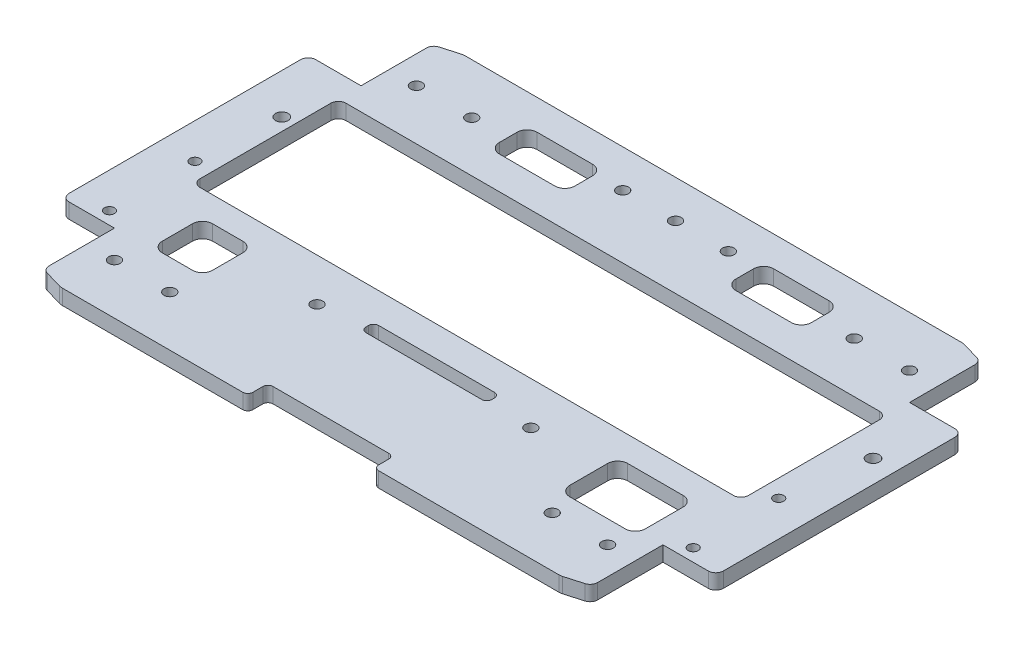
SolidWorks part; units mm, degrees
ref_plane "Plan de face" through (0, 0, 0) normal (0, 0, 1) x (1, 0, 0)
ref_plane "Plan de dessus" through (0, 0, 0) normal (0, 1, 0) x (1, 0, 0)
ref_plane "Plan de droite" through (0, 0, 0) normal (1, 0, 0) x (0, 0, -1)
sketch "Esquisse1" plane through (0, 0, 0) normal (0, 1, 0) x (1, 0, 0)
  line L0 (0, 0) -> (135, 0) construction
  line L1 (0, 0) -> (-135, 0) construction
  line L2 (-135, 0) -> (-135, -75)
  line L3 (-135, -85) -> (135, -85) construction
  line L4 (135, 0) -> (135, 75)
  line L5 (0, 85) -> (0, -85) construction
  line L6 (135, 85) -> (-135, 85) construction
  line L24 (0, -85) -> (-100, -85)
  line L26 (0, -85) -> (100, -85)
  line L28 (135, 0) -> (135, -75)
  line L31 (0, 85) -> (-100, 85)
  line L32 (0, 85) -> (100, 85)
  line L34 (-135, 0) -> (-135, 75)
  line L35 (-135, -75) -> (-100, -85)
  line L37 (-135, 75) -> (-100, 85)
  line L38 (100, 85) -> (135, 75)
  line L39 (100, -85) -> (135, -75)
  line L40 (-135, 75) -> (-100, 75) construction
  line L41 (-100, 75) -> (-100, 85) construction
  dimension "D1" = 10
  dimension "D2" = 200
  dimension "D3" = 10
  dimension "D4" = 200
  dimension "D5" = 75
  dimension "D6" = 35
  dimension "D7" = 75
  dimension "D8" = 170
extrude "Boss.-Extru.1" add sketch "Esquisse1" along normal blind 6
sketch "Esquisse15" plane through (0, 6, 0) normal (0, 1, 0) x (1, 0, 0)
  line L0 (-135, 60) -> (-135, 75)
  line L1 (-135, 60) -> (-120, 60) construction
  line L2 (-135, -60) -> (-120, -60) construction
  line L4 (-135, -60) -> (-135, -75)
  line L5 (-100, 85) -> (-135, 75) construction
  line L6 (-135, 75) -> (-135, -75) construction
  circle A0 centre (-120, 60) radius 2.3
  circle A1 centre (-120, -60) radius 2.3
extrude "Enlèv. mat.-Extru.6" cut sketch "Esquisse15" against normal up to next contours A1 | A0
mirror "Symétrie5" about plane through (0, 0, 0) normal (1, 0, 0) of "Enlèv. mat.-Extru.6"
sketch "Esquisse17" plane through (0, 6, 0) normal (0, 1, 0) x (1, 0, 0)
  line L0 (0, -85) -> (0, -71) construction
  line L1 (-100, -85) -> (100, -85) construction
  line L2 (-3.3, 0) -> (3.3, 0) construction
  line L4 (0, 85) -> (0, 71) construction
  circle A0 centre (0, -71) radius 2.3
  circle A3 centre (10, -71) radius 2.3
  circle A5 centre (-10, -71) radius 2.3
  circle A6 centre (30, -71) radius 2.3
  circle A7 centre (50, -71) radius 2.3
  circle A9 centre (90, -71) radius 2.3
  circle A11 centre (-50, -71) radius 2.3
  circle A13 centre (-90, -71) radius 2.3
  circle A14 centre (-90, 71) radius 2.3
  circle A16 centre (-50, 71) radius 2.3
  circle A17 centre (-30, 71) radius 2.3
  circle A18 centre (90, 71) radius 2.3
  circle A20 centre (50, 71) radius 2.3
  circle A21 centre (30, 71) radius 2.3
  circle A22 centre (-10, 71) radius 2.3
  circle A23 centre (10, 71) radius 2.3
  circle A24 centre (0, 71) radius 2.3
  circle A25 centre (-70, -71) radius 2.3 [skipped]
  circle A26 centre (70, -71) radius 2.3 [skipped]
  circle A27 centre (-70, -71) radius 2.3
  circle A28 centre (-30, -71) radius 2.3
  circle A29 centre (70, -71) radius 2.3
  circle A30 centre (70, 71) radius 2.3
  circle A31 centre (-70, 71) radius 2.3
  circle A32 centre (-30, -71) radius 2.3 [skipped]
  dimension "D1" = 2
  dimension "D3" = 2
  dimension "D2" = 5
  dimension "D4" = 5
  dimension "D5" = 2
  dimension "D6" = 2
  dimension "D7" = 2
  dimension "D8" = 2
sketch "Esquisse20" plane through (0, 6, 0) normal (0, 1, 0) x (1, 0, 0)
  line L0 (-120, -60) -> (-109, -60) construction
  line L1 (-109, -60) -> (-109, -82.4286)
  line L2 (-135, -75) -> (-100, -85) construction
  line L3 (-109, -60) -> (-109, -49)
  line L4 (-109, -49) -> (-135, -49)
  line L5 (-135, 75) -> (-135, -75) construction
  line L6 (-135, -49) -> (-135, -75)
  line L8 (-135, -75) -> (-109, -82.4286)
extrude "Enlèv. mat.-Extru.10" cut sketch "Esquisse20" against normal up to next
mirror "Symétrie7" about plane through (0, 0, 0) normal (1, 0, 0) of "Enlèv. mat.-Extru.10"
mirror "Symétrie8" about plane through (0, 0, 0) normal (0, 0, 1) of "Symétrie7", "Enlèv. mat.-Extru.10"
sketch "Esquisse26" plane through (0, 6, 0) normal (0, 1, 0) x (1, 0, 0)
  line L0 (135, 49) -> (130, 49)
  line L1 (109, 49) -> (135, 49) construction
  line L2 (130, 49) -> (130, -49)
  line L3 (109, -49) -> (135, -49) construction
  line L4 (130, -49) -> (135, -49)
  line L5 (135, -49) -> (135, 49)
  line L6 (-135, -49) -> (-130, -49)
  line L7 (-109, -49) -> (-135, -49) construction
  line L8 (-130, -49) -> (-130, 49)
  line L9 (-109, 49) -> (-135, 49) construction
  line L10 (-130, 49) -> (-135, 49)
  line L11 (-135, 49) -> (-135, -49)
  line L12 (100, -85) -> (109, -82.4286) construction
  line L13 (100, -85) -> (98.6264, -80.1924)
  line L14 (-100, -85) -> (100, -85)
  line L15 (107.6264, -77.621) -> (109, -77.2285)
  line L16 (-100, -85) -> (-100, -80)
  line L17 (100, -85) -> (100, -80)
  line L18 (100, -80) -> (-100, -80)
  line L19 (-109, -82.4286) -> (-107.6264, -77.621)
  line L20 (-107.6264, -77.621) -> (-98.6264, -80.1924)
  line L21 (109, -82.4286) -> (107.6264, -77.621)
  line L22 (98.6264, -80.1924) -> (107.6264, -77.621)
  line L23 (-109, -82.4286) -> (-100, -85) construction
  line L24 (-100, -85) -> (-98.6264, -80.1924)
  line L26 (109, -82.4286) -> (109, -49) construction
  line L32 (-3.3, 0) -> (3.3, 0) construction
  line L33 (-109, 77.2285) -> (-109, 82.4286)
  line L34 (-107.6264, 77.621) -> (-109, 77.2285)
  line L35 (109, 77.2285) -> (109, 82.4286)
  line L37 (-100, -85) -> (-109, -82.4286)
  line L38 (100, -85) -> (109, -82.4286)
  line L40 (100, 85) -> (109, 82.4286)
  line L45 (109, -77.2285) -> (109, -82.4286)
  line L47 (-107.6264, -77.621) -> (-109, -77.2285)
  line L48 (-109, -82.4286) -> (-109, -49) construction
  line L50 (-109, -77.2285) -> (-109, -82.4286)
  line L52 (-100, 85) -> (-109, 82.4286)
  line L55 (-100, 85) -> (-98.6264, 80.1924)
  line L56 (98.6264, 80.1924) -> (107.6264, 77.621)
  line L57 (109, 82.4286) -> (107.6264, 77.621)
  line L58 (-107.6264, 77.621) -> (-98.6264, 80.1924)
  line L59 (-109, 82.4286) -> (-107.6264, 77.621)
  line L60 (100, 80) -> (-100, 80)
  line L61 (100, 85) -> (100, 80)
  line L62 (-100, 85) -> (-100, 80)
  line L63 (107.6264, 77.621) -> (109, 77.2285)
  line L64 (-100, 85) -> (100, 85)
  line L65 (100, 85) -> (98.6264, 80.1924)
  line M92 (109, 49) -> (109, 82.4286)
  line M93 (109, 82.4286) -> (100, 85)
  line M94 (100, 85) -> (-100, 85)
  line M95 (-100, 85) -> (-109, 82.4286)
  line M96 (-109, 82.4286) -> (-109, 49)
  line M97 (-109, 49) -> (-135, 49)
  line M98 (-135, 49) -> (-135, -49)
  line M99 (-135, -49) -> (-109, -49)
  line M100 (-109, -49) -> (-109, -82.4286)
  line M101 (-109, -82.4286) -> (-100, -85)
  line M102 (-100, -85) -> (100, -85)
  line M103 (100, -85) -> (109, -82.4286)
  line M104 (109, -82.4286) -> (109, -49)
  line M105 (109, -49) -> (135, -49)
  line M106 (135, -49) -> (135, 49)
  line M107 (135, 49) -> (109, 49)
  dimension "D1" = 90
  dimension "D2" = 90
  dimension "D3" = 90
  dimension "D4" = 90
  dimension "D5" = 90
  dimension "D6" = 90
  dimension "D7" = 5
  dimension "D8" = 5
  dimension "D9" = 5
  dimension "D10" = 5
  dimension "D11" = 9.3601
extrude "Enlèv. mat.-Extru.12" cut sketch "Esquisse26" against normal up to next contours L20 L19 L16 L18 M101 | L19 L47 M100 | L24 L13 L22 L18 L20 M102 | L22 L18 L17 L21 M103 | L22 L13 L17 L18 | L21 L15 M104 | L2 M107 M105 M106 | L61 L60 L56 L57 M93 | L57 L63 M92 | L61 L65 L56 L60 | L65 L55 L58 L60 L56 M94 | L55 L62 L60 L58 | L62 L59 L58 L60 M95 | L59 L34 M96 | L8 M99 M97 M98 | L16 L24 L20 L18
sketch "Esquisse28" plane through (0, 6, 0) normal (0, 1, 0) x (1, 0, 0)
  line L0 (0, 0) -> (0, 40) construction
  line L1 (0, 0) -> (0, -18) construction
  line L2 (0, 40) -> (109, 40)
  line L3 (0, -18) -> (109, -18)
  line L4 (109, -18) -> (109, 40)
  line L5 (0, 40) -> (-109, 40)
  line L6 (-109, 40) -> (-109, -18)
  line L7 (-109, -18) -> (0, -18)
  dimension "D1" = 40
  dimension "D2" = 18
extrude "Enlèv. mat.-Extru.13" cut sketch "Esquisse28" against normal up to next
sketch "Esquisse30" plane through (0, 6, 0) normal (0, 1, 0) x (1, 0, 0)
  line L0 (-109, 40) -> (-109, -18) construction
  line L1 (-114, 22.5) -> (-109, 22.5) construction
  line L2 (-114, 22.5) -> (121, 22.5) construction
  line L3 (0, 22.5) -> (0, 40) construction
  line L5 (109, 40) -> (-109, 40) construction
  circle A0 centre (-114, 22.5) radius 2.5
  circle A1 centre (121, 22.5) radius 2.5
  dimension "D2" = 235
  dimension "D1" = 58
  dimension "D3" = 5
  dimension "D4" = 17.5
extrude "Enlèv. mat.-Extru.14" cut sketch "Esquisse30" against normal up to next
fillet "Congé1" radius 3 4 edges at (109, 3, -40) (109, 3, 18) (-109, 3, 18) (-109, 3, -40)
fillet "Congé2" radius 3 8 edges at (109, 3, 77.2285) (-109, 3, 77.2285) (-109, 3, -77.2285) (109, 3, -77.2285) (-130, 3, -49) (-130, 3, 49) (130, 3, 49) (130, 3, -49)
fillet "Congé3" radius 5 4 edges at (99.2997, 3, 80) (-99.2997, 3, 80) (99.2997, 3, -80) (-99.2997, 3, -80)
sketch "Esquisse31" plane through (0, 6, 0) normal (0, 1, 0) x (1, 0, 0)
  line L0 (0, 0) -> (0, -18) construction
  line L1 (-106, -18) -> (106, -18) construction
  line L2 (0, -18) -> (0, -28) construction
  line L4 (0, -28) -> (70, -28) construction
  line L5 (70, -28) -> (100, -28)
  line L6 (100, -28) -> (100, -51)
  line L7 (100, -51) -> (70, -51)
  line L16 (70, -51) -> (70, -28)
  dimension "D1" = 10
  dimension "D2" = 70
  dimension "D3" = 23
  dimension "D4" = 30
extrude "Enlèv. mat.-Extru.15" cut sketch "Esquisse31" against normal up to next contours L16 L7 L6 L5
sketch "Esquisse32" plane through (0, 6, 0) normal (0, 1, 0) x (1, 0, 0)
  line L0 (109, -60) -> (98, -60) construction
  line L2 (98, -60) -> (76, -60) construction
  line L3 (120, -60) -> (109, -60) construction
  line L4 (109, -74.9656) -> (109, -49) construction
  circle A2 centre (98, -60) radius 2.3
  circle A3 centre (76, -60) radius 2.3
  dimension "D1" = 11
  dimension "D2" = 22
extrude "Enlèv. mat.-Extru.16" cut sketch "Esquisse32" against normal up to next
mirror "Symétrie10" about plane through (0, 0, 0) normal (0, 0, 1) of "Enlèv. mat.-Extru.16"
mirror "Symétrie11" about plane through (0, 0, 0) normal (1, 0, 0) of "Symétrie10", "Enlèv. mat.-Extru.16"
sketch "Esquisse33" plane through (0, 6, 0) normal (0, 1, 0) x (1, 0, 0)
  line L0 (-109, -49) -> (-130, -49) construction
  line L1 (-130, -49) -> (-130, -39) construction
  line L2 (-130, -46) -> (-130, 46) construction
  line L3 (-130, -39) -> (-130, -15) construction
  line L4 (-130, -27) -> (-116, -27) construction
  line L5 (-116, -27) -> (-116, -44) construction
  line L6 (-116, -27) -> (-116, -10) construction
  circle A0 centre (-116, -44) radius 2
  circle A1 centre (-116, -10) radius 2
  dimension "D4" = 17
  dimension "D5" = 22
  dimension "D1" = 10
  dimension "D2" = 14
  dimension "D3" = 24
extrude "Enlèv. mat.-Extru.17" cut sketch "Esquisse33" against normal up to next
mirror "Symétrie12" about plane through (0, 0, 0) normal (1, 0, 0) of "Enlèv. mat.-Extru.17"
sketch "Esquisse34" plane through (0, 6, 0) normal (0, 1, 0) x (1, 0, 0)
  line L0 (0, 80) -> (0, 65) construction
  line L2 (98.5995, 80) -> (-98.5995, 80) construction
  line L3 (0, 65) -> (21, 65) construction
  line L4 (0, 65) -> (-21, 65) construction
  circle A0 centre (21, 65) radius 2.3
  circle A1 centre (-21, 65) radius 2.3
  circle A2 centre (0, 65) radius 2.3
  dimension "D1" = 21
  dimension "D2" = 15
  dimension "D3" = 21
extrude "Enlèv. mat.-Extru.18" cut sketch "Esquisse34" against normal up to next
fillet "Congé4" radius 4 4 edges at (70, 3, 51) (100, 3, 51) (100, 3, 28) (70, 3, 28)
sketch "Esquisse35" plane through (0, 6, 0) normal (0, 1, 0) x (1, 0, 0)
  line L0 (0, 0) -> (0, -28) construction
  line L1 (0, -28) -> (-75, -28) construction
  line L2 (-75, -28) -> (-95, -28)
  line L3 (-95, -28) -> (-95, -48)
  line L4 (-95, -48) -> (-75, -48)
  line L5 (-75, -48) -> (-75, -28)
  dimension "D1" = 28
  dimension "D2" = 75
  dimension "D3" = 20
extrude "Enlèv. mat.-Extru.19" cut sketch "Esquisse35" against normal up to next
fillet "Congé5" radius 4 4 edges at (-75, 3, 28) (-75, 3, 48) (-95, 3, 48) (-95, 3, 28)
sketch "Esquisse36" plane through (0, 6, 0) normal (0, 1, 0) x (1, 0, 0)
  line L0 (0, 80) -> (-50, 80) construction
  line L1 (98.5995, 80) -> (-98.5995, 80) construction
  line L2 (-50, 80) -> (-50, 68) construction
  line L3 (-50, 68) -> (-32, 68)
  line L4 (-32, 68) -> (-32, 53)
  line L5 (-32, 53) -> (-62, 53)
  line L6 (-62, 53) -> (-62, 68)
  line L7 (-62, 68) -> (-50, 68)
  line L8 (0, -3.3) -> (0, 3.3) construction
  line L9 (50, 80) -> (50, 68) construction
  line L10 (62, 68) -> (50, 68)
  line L11 (62, 53) -> (62, 68)
  line L12 (32, 53) -> (62, 53)
  line L13 (32, 68) -> (32, 53)
  line L14 (50, 68) -> (32, 68)
  dimension "D1" = 12
  dimension "D2" = 12
  dimension "D3" = 18
extrude "Enlèv. mat.-Extru.20" cut sketch "Esquisse36" against normal up to next
fillet "Congé6" radius 4 8 edges at (32, 3, -68) (32, 3, -53) (62, 3, -53) (62, 3, -68) (-32, 3, -68) (-32, 3, -53) (-62, 3, -53) (-62, 3, -68)
sketch "Esquisse37" plane through (0, 6, 0) normal (0, 1, 0) x (1, 0, 0)
  line L0 (0, 0) -> (0, -35) construction
  line L1 (0, -35) -> (42.5, -35) construction
  line L2 (0, -35) -> (-42.5, -35) construction
  circle A0 centre (-42.5, -35) radius 2.3
  circle A1 centre (42.5, -35) radius 2.3
  dimension "D1" = 42.5
  dimension "D2" = 35
  dimension "D3" = 42.5
extrude "Enlèv. mat.-Extru.21" cut sketch "Esquisse37" against normal through all
sketch "Esquisse38" plane through (0, 6, 0) normal (0, 1, 0) x (1, 0, 0)
  line L0 (0, -80) -> (0, -72) construction
  line L3 (0, 0) -> (0, -30) construction
  line L4 (0, -30) -> (0, -35) construction
  line L5 (0, -35) -> (25, -35)
  line L6 (25, -35) -> (25, -30)
  line L7 (25, -30) -> (-25, -30)
  line L8 (-25, -30) -> (-25, -35)
  line L9 (-25, -35) -> (0, -35)
  line L10 (98.5995, -80) -> (-98.5995, -80) construction
  line L11 (0, -72) -> (25, -72)
  line L12 (25, -72) -> (25, -80)
  line L13 (25, -80) -> (-25, -80)
  line L14 (-25, -80) -> (-25, -72)
  line L15 (-25, -72) -> (0, -72)
  dimension "D1" = 25
  dimension "D2" = 50
  dimension "D3" = 5
  dimension "D4" = 30
  dimension "D5" = 5
extrude "Enlèv. mat.-Extru.22" cut sketch "Esquisse38" against normal up to next
fillet "Congé7" radius 2 8 edges at (25, 3, 35) (25, 3, 30) (-25, 3, 35) (-25, 3, 30) (-25, 3, 72) (-25, 3, 80) (25, 3, 72) (25, 3, 80)
